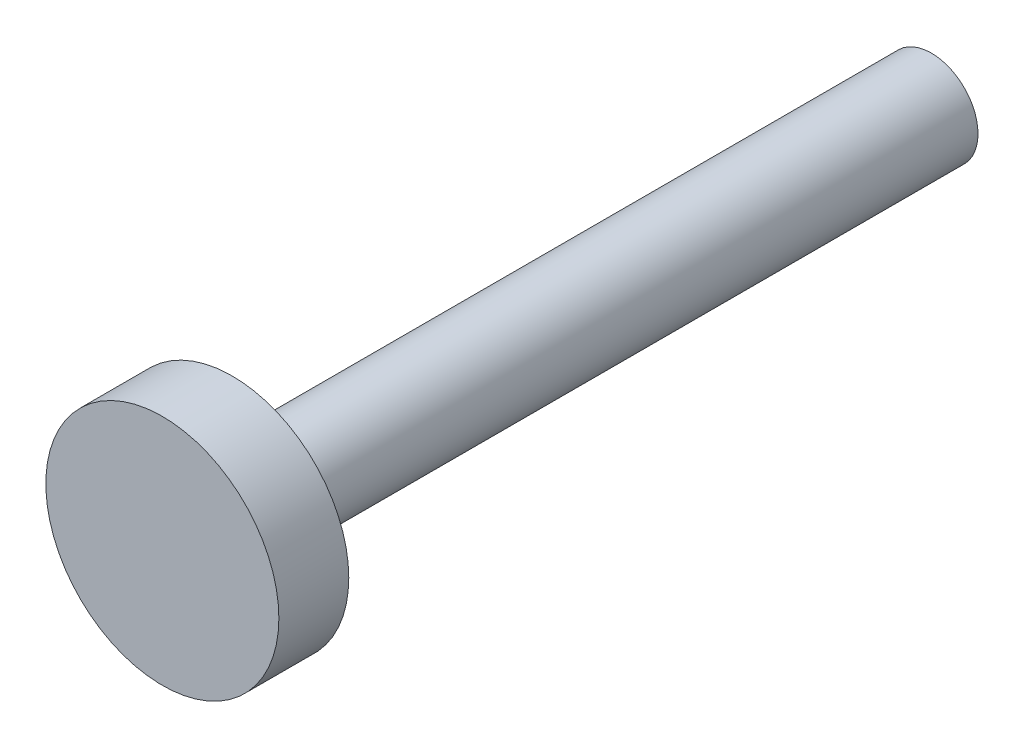
SolidWorks part; units mm, degrees
ref_plane "정면" through (0, 0, 0) normal (0, 0, 1) x (1, 0, 0)
ref_plane "윗면" through (0, 0, 0) normal (0, 1, 0) x (1, 0, 0)
ref_plane "우측면" through (0, 0, 0) normal (1, 0, 0) x (0, 0, -1)
sketch "스케치1" plane through (0, 0, 0) normal (0, 0, 1) x (1, 0, 0)
  circle A0 centre (0, 0) radius 2
  dimension "D1" = 4
extrude "보스-돌출1" add sketch "스케치1" along normal blind 30
sketch "스케치2" plane through (0, 0, 30) normal (0, 0, 1) x (1, 0, 0)
  circle A0 centre (0, 0) radius 5
  dimension "D1" = 10
extrude "보스-돌출2" add sketch "스케치2" along normal blind 3
